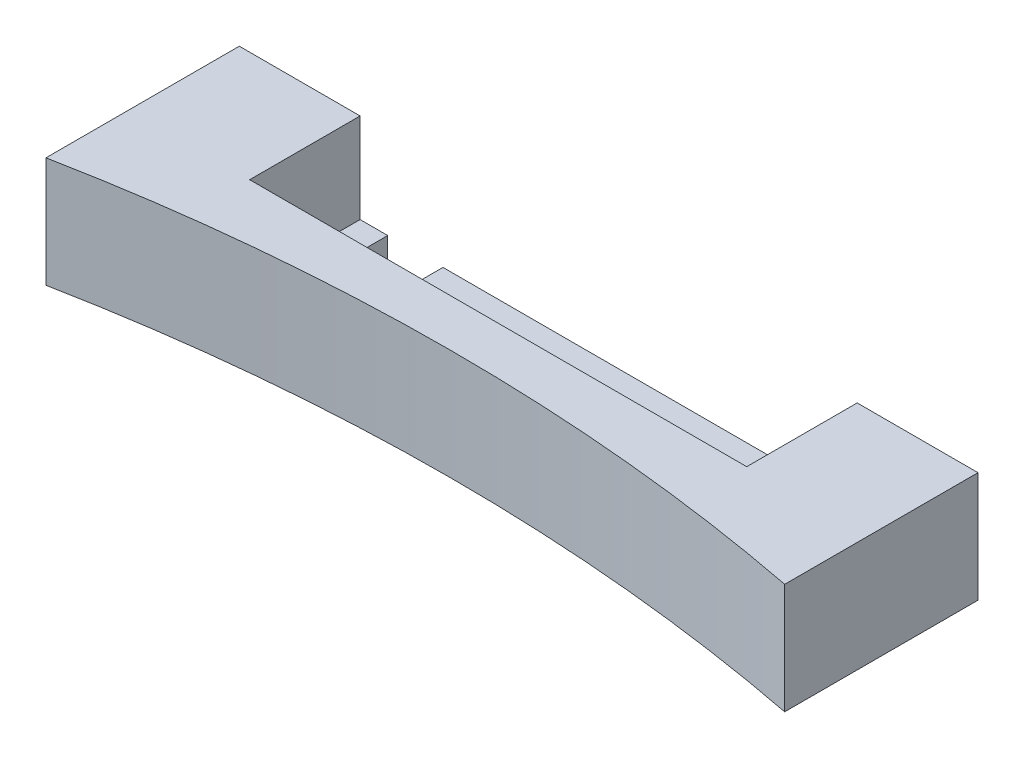
SolidWorks part; units mm, degrees
ref_plane "Front Plane" through (0, 0, 0) normal (0, 0, 1) x (1, 0, 0)
ref_plane "Top Plane" through (0, 0, 0) normal (0, 1, 0) x (1, 0, 0)
ref_plane "Right Plane" through (0, 0, 0) normal (1, 0, 0) x (0, 0, -1)
sketch "Sketch1" plane through (0, 0, 0) normal (0, 0, 1) x (1, 0, 0)
  line L0 (-18, 0) -> (-18, 6.5)
  line L1 (-18, 6.5) -> (-26.75, 6.5)
  line L2 (-26.75, 6.5) -> (-26.75, -1.5)
  line L3 (-26.75, -1.5) -> (26.75, -1.5)
  line L4 (26.75, -1.5) -> (26.75, 6.5)
  line L5 (26.75, 6.5) -> (18, 6.5)
  line L6 (18, 6.5) -> (18, 0)
  line L7 (18, 0) -> (-18, 0)
  line L8 (0, -55) -> (0, 55) construction
  line L9 (55, 0) -> (-55, 0) construction
  point P7 (0, 0)
  dimension "D1" = 36
  dimension "D2" = 6.5
  dimension "D3" = 1.5
  dimension "D4" = 53.5
extrude "Boss-Extrude1" add sketch "Sketch1" along normal blind 6
sketch "Sketch3" plane through (0, 0, 6) normal (0, 0, 1) x (1, 0, 0)
  line L1 (-26.75, 6.5) -> (26.75, 6.5)
  line L2 (-26.75, 6.5) -> (-26.75, -1.5)
  line L3 (-26.75, -1.5) -> (26.75, -1.5)
  line L4 (26.75, 6.5) -> (26.75, -1.5)
extrude "Boss-Extrude2" add sketch "Sketch3" along normal blind 2
hole_wizard "CSK for M3 Countersunk Flat Head Screw1" positions "Sketch4" profile "Sketch5" countersink size "M3" standard "ISO" end condition through all
sketch "Sketch4" plane through (0, -1.5, 0) normal (0, -1, 0) x (-1, 0, 0)
  line L1 (0, 55) -> (0, -55) construction
  line L2 (-55, 0) -> (55, 0) construction
  point P0 (0, -3)
  dimension "D1" = 3
sketch "Sketch5" plane through (0, -1.5, 3) normal (1, 0, 0) x (0, 0, -1)
  line L0 (0, 0) -> (0, 8)
  line L1 (0, 8) -> (1.8, 8)
  line L2 (1.8, 8) -> (1.8, 1.35)
  line L3 (1.8, 1.35) -> (3.15, 0)
  line L5 (3.15, 0) -> (0, 0)
  line L6 (-1.8, 1.35) -> (-3.15, 0) construction
  line L11 (0, -6.35) -> (0, 107.95) construction
  dimension "Thru Hole Dia." = 3.6
  dimension "Thru Hole Depth" = 8
  dimension "Near C'Sink Dia." = 6.3
  dimension "Near C'Sink Angle" = 90
sketch "Sketch6" plane through (0, 0, 0) normal (0, 1, 0) x (1, 0, 0)
  line L0 (14, 0) -> (14, -3) construction
  line L1 (16, 0) -> (16, -3)
  line L2 (12, 0) -> (12, -3)
  line L3 (18, 0) -> (-18, 0) construction
  line L4 (0, -55) -> (0, 55) construction
  line L5 (-14, 0) -> (-14, -3) construction
  line L6 (-16, 0) -> (-16, -3)
  line L7 (-12, 0) -> (-12, -3)
  arc A0 (16, 0) -> (12, 0) centre (14, 0) ccw
  arc A1 (12, -3) -> (16, -3) centre (14, -3) ccw
  circle A2 centre (0, -3) radius 1.8 construction
  arc A3 (-16, 0) -> (-12, 0) centre (-14, 0) cw
  arc A4 (-12, -3) -> (-16, -3) centre (-14, -3) cw
  point P2 (14, -1.5)
  point P18 (-14, -1.5)
  dimension "D1" = 14
  dimension "D2" = 4
  dimension "D3" = 3
extrude "Cut-Extrude1" cut sketch "Sketch6" against normal through all
sketch "Sketch7" plane through (0, -1.5, 0) normal (0, 1, 0) x (1, 0, 0)
  line L0 (26.75, -12) -> (26.75, -8)
  line L1 (-26.75, -12) -> (-26.75, -8)
  line L2 (-26.75, -8) -> (26.75, -8)
  arc A0 (26.75, -12) -> (-26.75, -12) centre (0, -149.4207) ccw
  dimension "D1" = 140
  dimension "D2" = 4
extrude "Boss-Extrude3" add sketch "Sketch7" along normal through all
sketch "Sketch8" plane through (0, 0, 0) normal (0, 0, -1) x (-1, 0, 0)
  line L0 (-26.75, 6.5) -> (-18, 6.5)
  line L1 (-18, 6.5) -> (-18, 0)
  line L2 (-18, 0) -> (-16, 0)
  line L3 (-16, 0) -> (-16, -1.5)
  line L4 (-16, -1.5) -> (-26.75, -1.5)
  line L5 (-26.75, -1.5) -> (-26.75, 6.5)
  line L6 (-12, 0) -> (-12, -1.5)
  line L7 (-12, -1.5) -> (12, -1.5)
  line L8 (12, -1.5) -> (12, 0)
  line L9 (12, 0) -> (-12, 0)
  line L10 (18, 6.5) -> (26.75, 6.5)
  line L11 (26.75, 6.5) -> (26.75, -1.5)
  line L12 (26.75, -1.5) -> (16, -1.5)
  line L13 (16, -1.5) -> (16, 0)
  line L14 (16, 0) -> (18, 0)
  line L15 (18, 0) -> (18, 6.5)
extrude "Boss-Extrude4" add sketch "Sketch8" along normal blind 2
hole_wizard "CSK for M3 Countersunk Flat Head Screw2" positions "Sketch9" profile "Sketch10" countersink size "M3" standard "DIN" end condition through all
sketch "Sketch9" plane through (0, -1.5, 0) normal (0, -1, 0) x (-1, 0, 0)
  point P0 (0, -3)
sketch "Sketch10" plane through (0, -1.5, 3) normal (1, 0, 0) x (0, 0, -1)
  line L0 (0, 0) -> (0, 8)
  line L1 (0, 8) -> (1.8, 8)
  line L2 (1.8, 8) -> (1.8, 1.35)
  line L3 (1.8, 1.35) -> (3.15, 0)
  line L5 (3.15, 0) -> (0, 0)
  line L6 (-1.8, 1.35) -> (-3.15, 0) construction
  line L11 (0, -6.35) -> (0, 107.95) construction
  dimension "Thru Hole Dia." = 3.6
  dimension "Thru Hole Depth" = 8
  dimension "Near C'Sink Dia." = 6.3
  dimension "Near C'Sink Angle" = 90
